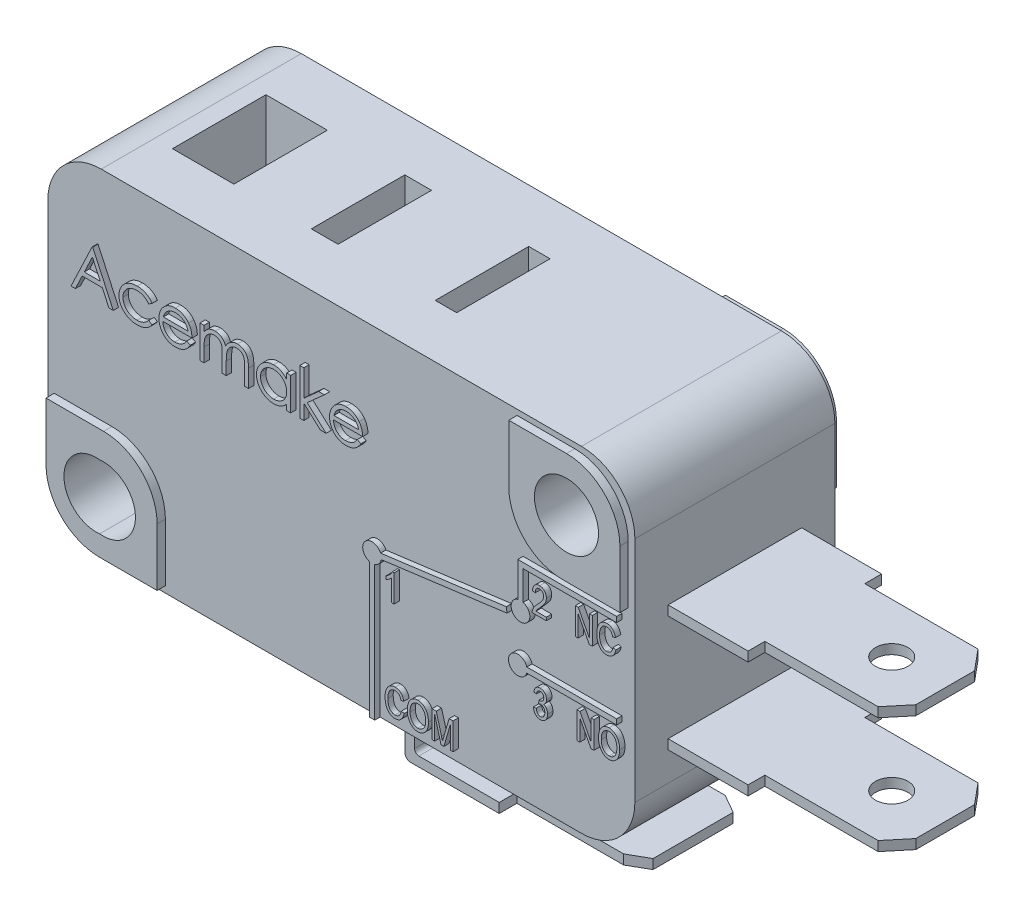
SolidWorks part; units mm, degrees
ref_plane "Front Plane" through (0, 0, 0) normal (0, 0, 1) x (1, 0, 0)
ref_plane "Top Plane" through (0, 0, 0) normal (0, 1, 0) x (1, 0, 0)
ref_plane "Right Plane" through (0, 0, 0) normal (1, 0, 0) x (0, 0, -1)
sketch "Sketch1" plane through (0, 0, 0) normal (0, 0, 1) x (1, 0, 0)
  line L1 (-11.4173, 7.9692) -> (11.4173, 7.9692)
  line L2 (-13.9573, 5.4292) -> (-13.9573, -5.4292)
  line L3 (-11.4173, -7.9692) -> (11.4173, -7.9692)
  line L4 (13.9573, 5.4292) -> (13.9573, -5.4292)
  line L5 (-13.9573, 7.9692) -> (13.9573, -7.9692) construction
  line L6 (-13.9573, -7.9692) -> (13.9573, 7.9692) construction
  arc A0 (13.9573, 5.4292) -> (11.4173, 7.9692) centre (11.4173, 5.4292) ccw
  arc A1 (13.9573, -5.4292) -> (11.4173, -7.9692) centre (11.4173, -5.4292) cw
  arc A2 (-11.4173, -7.9692) -> (-13.9573, -5.4292) centre (-11.4173, -5.4292) cw
  arc A3 (-13.9573, 5.4292) -> (-11.4173, 7.9692) centre (-11.4173, 5.4292) cw
  point P0 (0, 0)
  dimension "D2" = 27.9146
extrude "Boss-Extrude1" add sketch "Sketch1" against normal blind 9.5123
sketch "Sketch3" plane through (0, 0, 0) normal (0, 0, 1) x (1, 0, 0)
  line L0 (-13.6525, -2.3812) -> (-10.9093, -2.3812)
  line L1 (-11.4173, -7.9692) -> (11.4173, -7.9692) construction
  line L2 (-13.6525, -2.3812) -> (-13.6525, -5.1244)
  line L4 (-13.9573, 5.4292) -> (-13.9573, -5.4292) construction
  line L5 (-11.1125, -7.6644) -> (-8.3693, -7.6644)
  line L6 (-8.3693, -4.9213) -> (-8.3693, -7.6644)
  line L7 (13.6399, 2.428) -> (13.6399, 5.1712)
  line L8 (13.6399, 2.428) -> (10.8967, 2.428)
  line L9 (11.0999, 7.7112) -> (8.3567, 7.7112)
  line L10 (8.3567, 4.968) -> (8.3567, 7.7112)
  arc A0 (-11.1125, -7.6644) -> (-13.6525, -5.1244) centre (-11.1125, -5.1244) cw
  arc A1 (-8.3693, -4.9213) -> (-10.9093, -2.3812) centre (-10.9093, -4.9212) ccw
  arc A2 (11.0999, 7.7112) -> (13.6399, 5.1712) centre (11.0999, 5.1712) cw
  arc A3 (8.3567, 4.968) -> (10.8967, 2.428) centre (10.8967, 4.968) ccw
  dimension "D4" = 2.54
  dimension "D6" = 2.54
  dimension "D1" = 5.588
  dimension "D2" = 0.3048
  dimension "D3" = 0.3048
  dimension "D5" = 5.588
extrude "Boss-Extrude2" add sketch "Sketch3" along normal blind 0.3937 and the other way offset from surface (9.906 mm away) 0.3937 other way up to face at (0, 0, -9.5123)
sketch "Sketch2" plane through (0, 0, 0) normal (0, 0, 1) x (1, 0, 0)
  line L0 (-12.7998, -5.1712) -> (-9.4, -5.1712) construction
  line L3 (11.4173, 7.9692) -> (-11.4173, 7.9692) construction
  line L4 (-11.4173, -7.9692) -> (11.4173, -7.9692) construction
  line L5 (-11.0999, -5.1712) -> (-11.0999, -7.9692) construction
  line L6 (11.0999, 5.1712) -> (11.0999, 7.9692) construction
  circle A0 centre (-11.0999, -5.1712) radius 1.524 construction
  circle A1 centre (11.0999, 5.1712) radius 1.524
  arc A2 (-11.0999, -3.6472) -> (-11.0999, -6.6952) centre (-10.9331, -5.1712) cw
  arc A3 (-11.0999, -3.6472) -> (-11.0999, -6.6952) centre (-11.2667, -5.1712) ccw
  dimension "D1" = 3.048
  dimension "D2" = 3.048
  dimension "D3" = 1.5331
  dimension "D4" = 1.5331
extrude "Cut-Extrude1" cut sketch "Sketch2" against normal up to next and the other way blind 0.4064
sketch "Sketch4" plane through (0, 0, 0) normal (0, 0, 1) x (1, 0, 0)
  line L0 (13.3446, 2.0527) -> (8.6456, 2.0527)
  line L1 (8.6456, 2.0527) -> (8.6456, 0.4086)
  line L2 (1.5875, -7.9692) -> (1.5875, -1.5581)
  line L3 (13.3446, -2.1637) -> (9.0716, -2.1637)
  line L4 (-11.4173, -7.9692) -> (11.4173, -7.9692) construction
  line L5 (13.9573, -5.4292) -> (13.9573, 5.4292) construction
  line L7 (8.6456, -2.1637) -> (8.6456, -2.4177) construction
  line L8 (2.1203, -0.9508) -> (8.0976, -0.1663)
  line L9 (1.5875, -7.9692) -> (1.8415, -7.9692)
  line L10 (1.8415, -1.5581) -> (1.8415, -7.9692)
  line L11 (5.1496, -0.8094) -> (8.1307, -0.4182)
  line L12 (9.0716, -2.4177) -> (13.3446, -2.4177)
  line L13 (5.1496, -0.8094) -> (2.1534, -1.2026)
  line L15 (8.6456, -0.0174) -> (8.8996, -0.0174) construction
  line L16 (8.0976, -0.1663) -> (8.1307, -0.4182)
  line L17 (8.8996, 0.4086) -> (8.8996, 1.7987)
  line L18 (8.8996, 1.7987) -> (13.3446, 1.7987)
  line L19 (13.3446, 1.7987) -> (13.3446, 2.0527)
  line L20 (13.3446, -2.4177) -> (13.3446, -2.1637)
  circle A0 centre (8.7726, -0.0174) radius 0.4445
  circle A1 centre (8.6456, -2.2907) radius 0.4445
  circle A2 centre (1.7145, -1.1321) radius 0.4445
  line M20 (-11.4173, -7.9692) -> (11.4173, -7.9692)
  dimension "D1" = 0.889
  dimension "D2" = 0.889
  dimension "D4" = 0.889
  dimension "D3" = 12.3698
extrude "Boss-Extrude5" add sketch "Sketch4" along normal blind 0.254 contours A2 L2 L10 M20 | A2 | A2 L13 L11 L16 L8 | A0 | A0 L17 L18 L19 L0 L1 | A1 | A1 L12 L20 L3
sketch "Sketch5" plane through (0, 0, 0.254) normal (0, 0, 1) x (1, 0, 0)
  text T0 "Acemake" font "Century Gothic" height in points 8
  text T1 "COM" font "Arial Narrow" height 1.27
  text T2 "NC" font "Arial Narrow" height 1.27
  text T3 "2" font "Arial Narrow" height 1.27
  text T4 "3" font "Arial Narrow" height 1.27
  text T5 "NO" font "Arial Narrow" height 1.27
  text T6 "1" font "Arial Narrow" height 1.27
extrude "Boss-Extrude6" add sketch "Sketch5" against normal blind 0.254 separate body
sketch "Sketch6" plane through (13.9573, 0, 0) normal (1, 0, 0) x (0, 0, -1)
  line L0 (4.7562, 1.6902) -> (4.7562, -3.8216) construction
  line L1 (-0.6943, 1.9188) -> (9.8935, 1.9188) construction
  line L4 (4.7561, 5.4292) -> (4.7561, 1.9188) construction
  line L5 (1.5811, -3.593) -> (7.9312, -3.593)
  line L6 (1.5811, -3.593) -> (1.5811, -4.0502)
  line L7 (1.5811, -4.0502) -> (7.9312, -4.0502)
  line L8 (7.9312, -3.593) -> (7.9312, -4.0502)
  line L9 (1.5811, -3.593) -> (7.9312, -4.0502) construction
  line L10 (1.5811, -4.0502) -> (7.9312, -3.593) construction
  line L11 (1.5812, 1.9188) -> (7.9311, 1.9188)
  line L13 (1.5812, 1.9188) -> (1.5812, 1.4616)
  line L14 (1.5812, 1.4616) -> (7.9311, 1.4616)
  line L15 (7.9311, 1.9188) -> (7.9311, 1.4616)
  line L16 (1.5812, 1.9188) -> (7.9311, 1.4616) construction
  line L17 (1.5812, 1.4616) -> (7.9311, 1.9188) construction
  line L18 (9.5123, 5.4292) -> (0, 5.4292) construction
extrude "Boss-Extrude7" add sketch "Sketch6" along normal blind 10
sketch "Sketch7" plane through (0, 1.9188, 0) normal (0, 1, 0) x (1, 0, 0)
  line L0 (23.9573, 4.7562) -> (21.4173, 4.7562) construction
  line L1 (23.1445, 2.3813) -> (23.1445, 7.1311) construction
  line L2 (23.1445, 2.3813) -> (17.7597, 2.3813)
  line L3 (23.1445, 7.1311) -> (17.7597, 7.1311)
  line L4 (23.9573, 3.3592) -> (23.9573, 6.1532)
  line L5 (23.9573, 4.7562) -> (23.1445, 4.7562)
  line L6 (23.1445, 2.3813) -> (23.9573, 3.3592)
  line L7 (23.1445, 7.1311) -> (23.9573, 6.1532)
  line L8 (17.7597, 2.3813) -> (17.7597, 1.5812)
  line L9 (23.9573, 1.5812) -> (13.9573, 1.5812) construction
  line L10 (17.7597, 1.5812) -> (23.9573, 1.5812)
  line L11 (23.9573, 1.5812) -> (23.9573, 7.9311)
  line L12 (23.9573, 7.9311) -> (17.7597, 7.9311)
  line L13 (23.9573, 7.9311) -> (13.9573, 7.9311) construction
  line L14 (17.7597, 7.9311) -> (17.7597, 7.1311)
  circle A0 centre (21.4173, 4.7562) radius 0.7747
  line M2 (13.9573, 1.5812) -> (23.9573, 1.5812)
  line M3 (23.9573, 1.5812) -> (23.9573, 7.9311)
  line M4 (23.9573, 7.9311) -> (13.9573, 7.9311)
  dimension "D1" = 6.1976
extrude "Cut-Extrude2" cut sketch "Sketch7" against normal through all and the other way through all contours L2 L8 L6 M2 M3 | L14 L3 L7 M4 M3 | A0
sketch "Sketch8" plane through (0, 0, 0) normal (0, 0, 1) x (1, 0, 0)
  line L0 (1.3721, -7.9657) -> (1.3721, -10.4938)
  line L1 (1.638, -10.7597) -> (11.8248, -10.7597)
  line L2 (1.3721, -7.9657) -> (1.8293, -7.9657)
  line L3 (11.8248, -10.7597) -> (11.8248, -10.3025)
  line L4 (11.8248, -10.3025) -> (2.0325, -10.3025)
  line L5 (1.8293, -10.0993) -> (1.8293, -7.9657)
  arc A0 (1.8293, -10.0993) -> (2.0325, -10.3025) centre (2.0325, -10.0993) ccw
  arc A1 (1.638, -10.7597) -> (1.3721, -10.4938) centre (1.638, -10.4938) cw
  dimension "D1" = 0.4572
  dimension "D3" = 2.794
extrude "Boss-Extrude8" add sketch "Sketch8" against normal blind 6.5024 from offset 1.651 offset against normal yes
sketch "Sketch9" plane through (0, -10.7597, 0) normal (0, -1, 0) x (1, 0, 0)
  line L0 (11.8248, -4.9022) -> (10.9358, -4.9022) construction
  line L1 (11.8248, -8.1534) -> (11.8248, -1.651) construction
  line L2 (10.9358, -2.4892) -> (10.9358, -7.3152) construction
  line L3 (11.8248, -2.9972) -> (11.8248, -6.8072)
  line L4 (10.9358, -2.4892) -> (11.8248, -2.9972)
  line L5 (11.8248, -6.8072) -> (10.9358, -7.3152)
  line L6 (10.9358, -7.3152) -> (5.8558, -7.3152)
  line L7 (10.9358, -2.4892) -> (5.8558, -2.4892)
  line L8 (5.8558, -2.4892) -> (5.8558, -1.651)
  line L9 (1.638, -1.651) -> (11.8248, -1.651) construction
  line L10 (5.8558, -1.651) -> (11.8248, -1.651)
  line L11 (11.8248, -1.651) -> (11.8248, -8.1534)
  line L12 (1.638, -8.1534) -> (11.8248, -8.1534) construction
  line L13 (11.8248, -8.1534) -> (5.8558, -8.1534)
  line L14 (5.8558, -8.1534) -> (5.8558, -7.3152)
  line L15 (11.8248, -4.9022) -> (9.2848, -4.9022) construction
  circle A0 centre (9.2848, -4.9022) radius 0.7747
  line M1 (11.8248, -1.651) -> (1.638, -1.651)
  line M3 (1.638, -8.1534) -> (11.8248, -8.1534)
  line M4 (11.8248, -8.1534) -> (11.8248, -1.651)
  dimension "D1" = 5.969
extrude "Cut-Extrude3" cut sketch "Sketch9" against normal up to surface (0.4572 mm away) contours A0 | L8 L7 L4 M4 M1 | L14 L5 L6 M3 M4 up to face at (6.9286, -10.3025, -4.9022)
sketch "Sketch12" plane through (0, 7.9692, 0) normal (0, 1, 0) x (1, 0, 0)
  line L0 (-11.4173, 4.7561) -> (11.4173, 4.7561) construction
  line L1 (-11.4173, 9.5123) -> (-11.4173, 0) construction
  line L2 (11.4173, 9.5123) -> (11.4173, 0) construction
  line L3 (-7.6446, 4.7561) -> (-3.9616, 4.7561) construction
  line L10 (-3.9616, 6.9786) -> (-2.6916, 6.9786)
  line L11 (-3.9616, 6.9786) -> (-2.6916, 2.5336) construction
  line L12 (-3.9616, 6.9786) -> (-3.9616, 2.5336)
  line L13 (-3.9616, 2.5336) -> (-2.6916, 2.5336)
  line L14 (-3.9616, 2.5336) -> (-2.6916, 6.9786) construction
  line L15 (-2.6916, 6.9786) -> (-2.6916, 2.5336)
  line L22 (-2.6916, 4.7561) -> (1.9312, 4.7561) construction
  line L23 (2.9472, 6.9786) -> (2.9472, 2.5336)
  line L24 (1.9312, 6.9786) -> (2.9472, 6.9786)
  line L25 (1.9312, 6.9786) -> (2.9472, 2.5336) construction
  line L26 (1.9312, 2.5336) -> (2.9472, 2.5336)
  line L27 (1.9312, 6.9786) -> (1.9312, 2.5336)
  line L28 (1.9312, 2.5336) -> (2.9472, 6.9786) construction
  line L29 (-10.5656, 2.5336) -> (-7.6446, 6.9787) construction
  line L30 (-10.5656, 6.9787) -> (-10.5656, 2.5336)
  line L31 (-10.5656, 2.5336) -> (-7.6446, 2.5336)
  line L32 (-7.6446, 6.9787) -> (-7.6446, 2.5336)
  line L33 (-10.5656, 6.9787) -> (-7.6446, 2.5336) construction
  line L34 (-10.5656, 6.9787) -> (-7.6446, 6.9787)
  point P11 (-3.3266, 4.7561)
  point P25 (2.4392, 4.7561)
  point P30 (-9.1051, 4.7561)
extrude "Cut-Extrude4" cut sketch "Sketch12" against normal blind 2.9972
